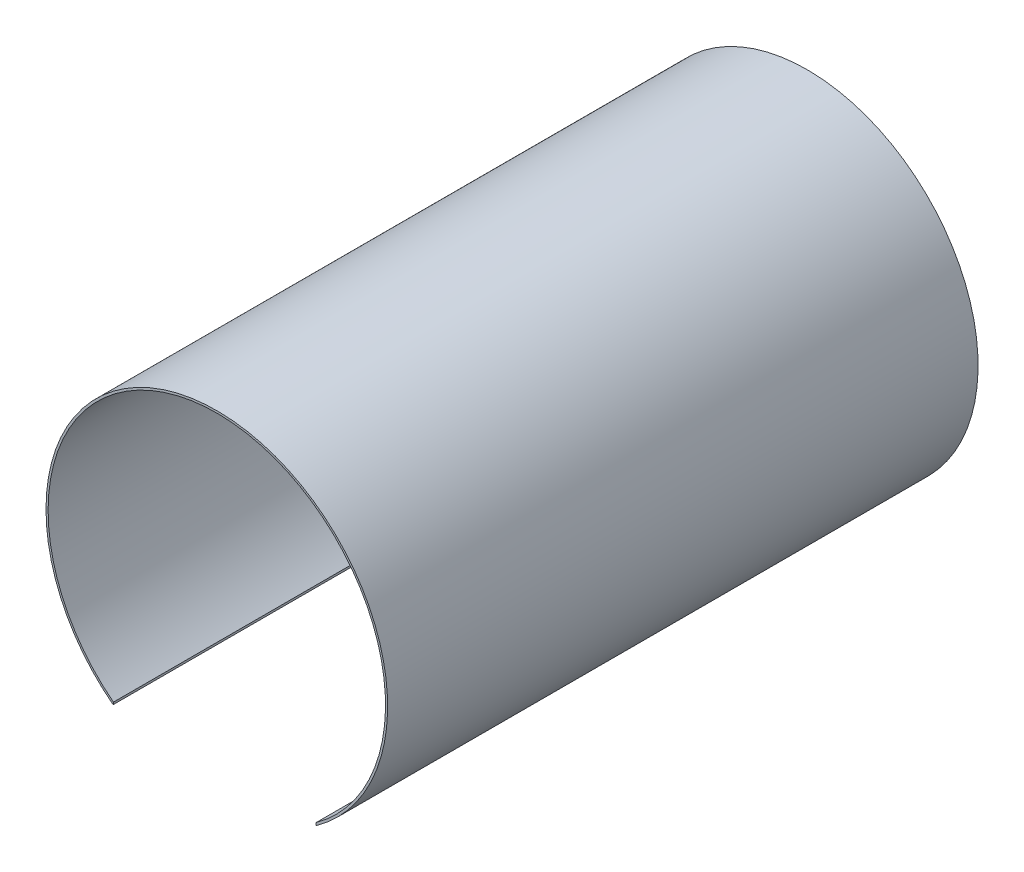
SolidWorks part; units mm, degrees
ref_plane "Front Plane" through (0, 0, 0) normal (0, 0, 1) x (1, 0, 0)
ref_plane "Top Plane" through (0, 0, 0) normal (0, 1, 0) x (1, 0, 0)
ref_plane "Right Plane" through (0, 0, 0) normal (1, 0, 0) x (0, 0, -1)
sketch "Sketch2" plane through (0, 0, 0) normal (0, 0, 1) x (1, 0, 0)
  line L0 (-155.6236, -200.7419) -> (149.1764, -205.5782)
  arc A0 (149.1764, -205.5782) -> (-155.6236, -200.7419) centre (0, 0) ccw
  dimension "D1" = 304.8
extrude "Extrude-Thin1" add sketch "Sketch2" along normal blind 889 thin
sketch "Sketch5" plane through (-3.2236, -203.16, 0) normal (0.0159, 0.9999, 0) x (0.9999, -0.0159, 0)
  line L1 (152.4192, -889) -> (-152.4192, -889)
  line L2 (152.4192, -889) -> (152.4192, 0)
  line L3 (152.4192, 0) -> (-152.4192, 0)
  line L4 (-152.4192, -889) -> (-152.4192, 0)
extrude "Cut-Extrude1" cut sketch "Sketch5" against normal through all
